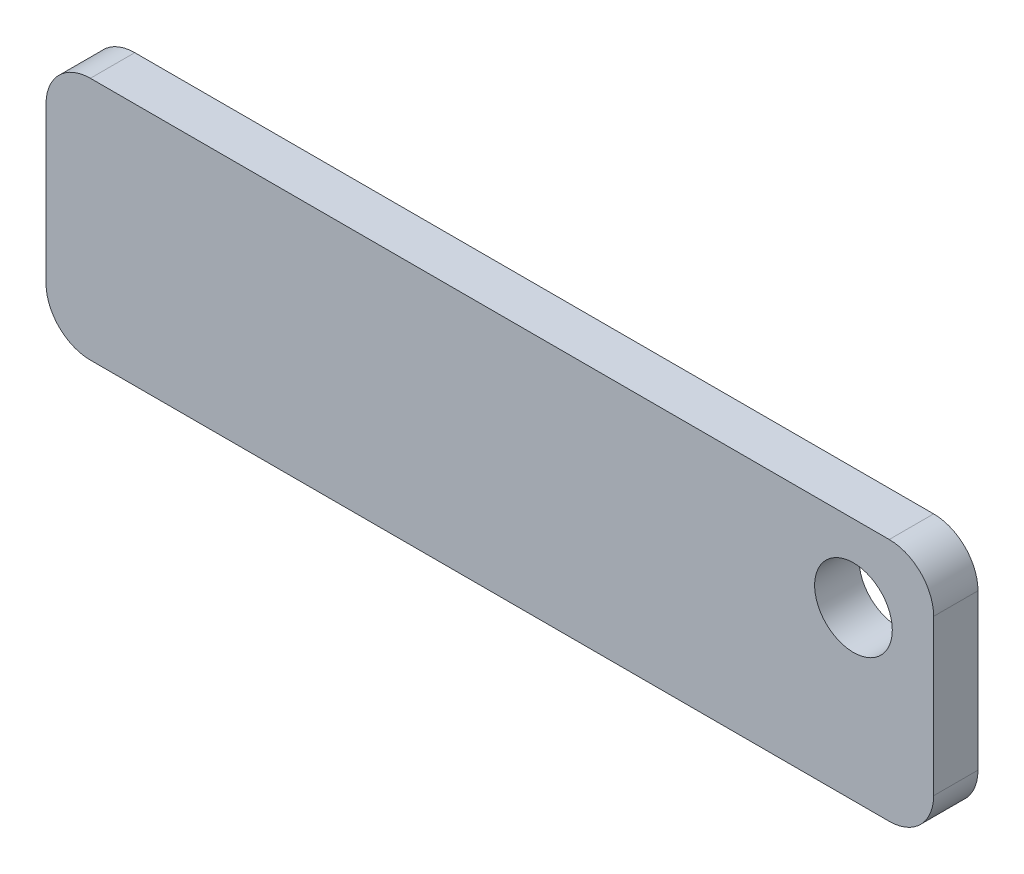
SolidWorks part; units mm, degrees
ref_plane "Front Plane" through (0, 0, 0) normal (0, 0, 1) x (1, 0, 0)
ref_plane "Top Plane" through (0, 0, 0) normal (0, 1, 0) x (1, 0, 0)
ref_plane "Right Plane" through (0, 0, 0) normal (1, 0, 0) x (0, 0, -1)
sketch "Sketch2" plane through (0, 0, 0) normal (0, 0, 1) x (1, 0, 0)
  line L1 (-18, 5.5) -> (18, 5.5)
  line L2 (-20, 3.5) -> (-20, -3.5)
  line L3 (-18, -5.5) -> (18, -5.5)
  line L4 (20, 3.5) -> (20, -3.5)
  line L5 (-20, 5.5) -> (20, -5.5) construction
  line L6 (-20, -5.5) -> (20, 5.5) construction
  arc A0 (18, 5.5) -> (20, 3.5) centre (18, 3.5) cw
  arc A1 (18, -5.5) -> (20, -3.5) centre (18, -3.5) ccw
  arc A2 (-20, -3.5) -> (-18, -5.5) centre (-18, -3.5) ccw
  arc A3 (-18, 5.5) -> (-20, 3.5) centre (-18, 3.5) ccw
  point P0 (0, 0)
  dimension "D3" = 2
  dimension "D1" = 40
  dimension "D2" = 11
extrude "Boss-Extrude2" add sketch "Sketch2" along normal blind 2
sketch "Sketch3" plane through (0, 0, 2) normal (0, 0, 1) x (1, 0, 0)
  circle A0 centre (16.3879, 2.034) radius 1.75
  point P2 (15.6661, 1.7609)
  point P3 (16.3879, 2.034)
  dimension "D1" = 3.5
extrude "Cut-Extrude1" cut sketch "Sketch3" against normal through all
